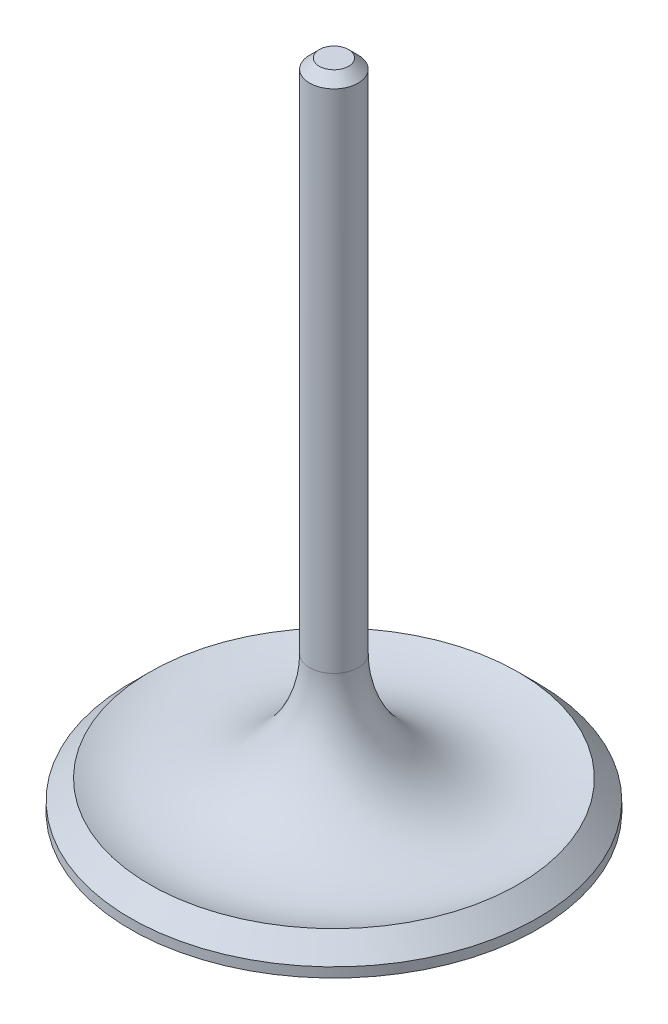
SolidWorks part; units mm, degrees
material "1.5714 (16NiCr4)"
ref_plane "Front Plane" through (0, 0, 0) normal (0, 0, 1) x (1, 0, 0)
ref_plane "Top Plane" through (0, 0, 0) normal (0, 1, 0) x (1, 0, 0)
ref_plane "Right Plane" through (0, 0, 0) normal (1, 0, 0) x (0, 0, -1)
sketch "Sketch1" plane through (0, 0, 0) normal (1, 0, 0) x (0, 0, -1)
  line L0 (0, 0) -> (0, 2172.97)
  line L1 (0, 2172.97) -> (80.772, 2172.97)
  line L2 (80.772, 2172.97) -> (80.772, 456.0493)
  line L3 (612.902, 96.774) -> (677.418, 32.258)
  line L4 (0, 0) -> (677.418, 0)
  line L5 (677.418, 0) -> (677.418, 32.258)
  arc A0 (80.772, 456.0493) -> (612.902, 96.774) centre (468.122, 456.0493) ccw
  dimension "D1" = 2172.97
  dimension "D7" = 387.35
  dimension "D2" = 677.418
  dimension "D3" = 80.772
  dimension "D4" = 32.258
  dimension "D5" = 96.774
  dimension "D6" = 45
revolve "Revolve1" add sketch "Sketch1" angle 360 about L0
chamfer "Chamfer1" distance 32.258 angle 45 1 edges at (0, 2172.97, -80.772)
scale "Scale1" scale about centroid uniform scaling yes scale factor 0.03937
